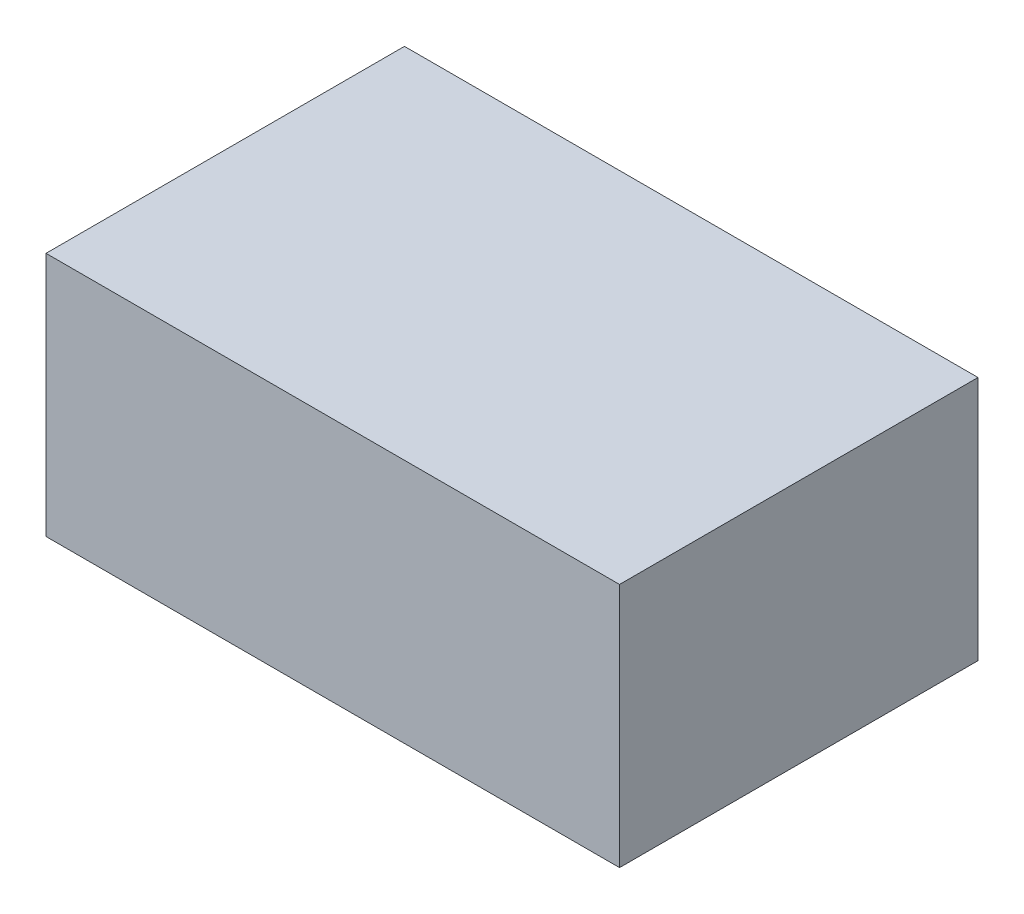
SolidWorks part; units mm, degrees
ref_plane "前视基准面" through (0, 0, 0) normal (0, 0, 1) x (1, 0, 0)
ref_plane "上视基准面" through (0, 0, 0) normal (0, 1, 0) x (1, 0, 0)
ref_plane "右视基准面" through (0, 0, 0) normal (1, 0, 0) x (0, 0, -1)
sketch "草图1" plane through (0, 0, 0) normal (0, 0, 1) x (1, 0, 0)
  line L1 (76, -32.5) -> (-76, -32.5)
  line L2 (76, -32.5) -> (76, 32.5)
  line L3 (76, 32.5) -> (-76, 32.5)
  line L4 (-76, -32.5) -> (-76, 32.5)
  point P0 (0, 0)
  dimension "D1" = 152
  dimension "D2" = 65
extrude "凸台-拉伸1" add sketch "草图1" along normal blind 95
